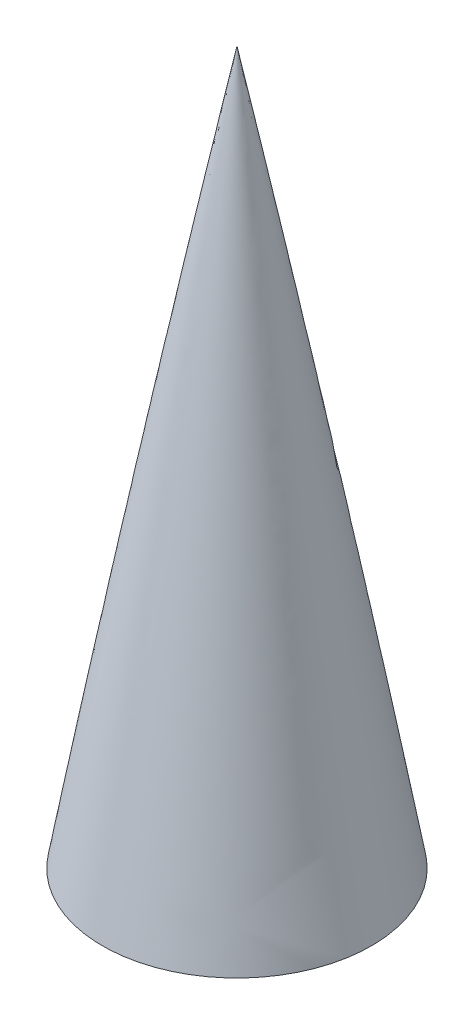
SolidWorks part; units mm, degrees
material "6061-T6 (SS)"
ref_plane "Front Plane" through (0, 0, 0) normal (0, 0, 1) x (1, 0, 0)
ref_plane "Top Plane" through (0, 0, 0) normal (0, 1, 0) x (1, 0, 0)
ref_plane "Right Plane" through (0, 0, 0) normal (1, 0, 0) x (0, 0, -1)
sketch "Sketch1" plane through (0, 0, 0) normal (0, 0, 1) x (1, 0, 0)
  line L0 (2626.36, 0) -> (2607.056, 0) construction
  line L1 (2607.056, 0) -> (2606.04, 0)
  line L2 (2606.04, -33.7223) -> (2606.04, 0) construction
  line L3 (2626.36, 203.2) -> (2626.36, 0) construction
  line L7 (2621.5608, 177.8) -> (2626.36, 177.8)
  line L9 (2626.36, 177.8) -> (2626.36, 203.2)
  arc A0 (2606.04, 0) -> (2626.36, 203.2) centre (3632.2, 0) cw construction
  arc A8 (2621.5608, 177.8) -> (2626.36, 203.2) centre (3632.2, 0) cw
  dimension "D1" = 20.32
  dimension "D2" = 19.304
  dimension "D3" = 203.2
  dimension "D4" = 25.4
revolve "Revolve1" add sketch "Sketch1" angle 360 about L9
